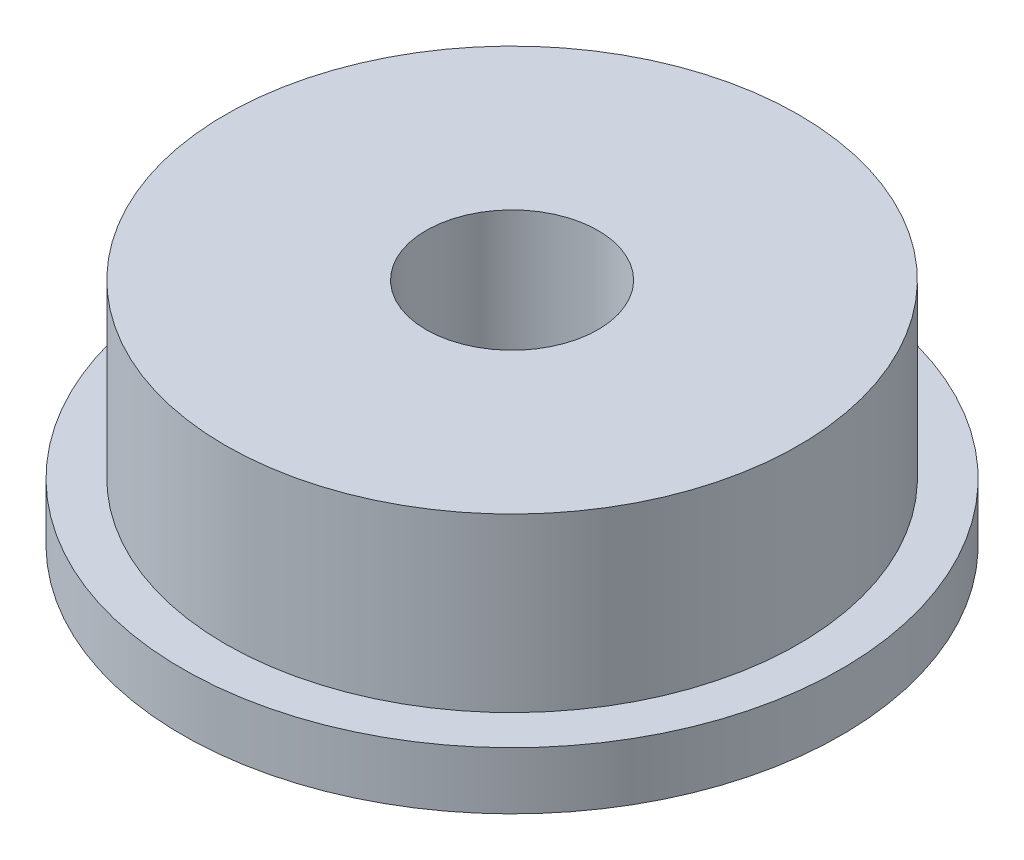
SolidWorks part; units mm, degrees
material "Liga de aço"
ref_plane "Plano frontal" through (0, 0, 0) normal (0, 0, 1) x (1, 0, 0)
ref_plane "Plano superior" through (0, 0, 0) normal (0, 1, 0) x (1, 0, 0)
ref_plane "Plano direito" through (0, 0, 0) normal (1, 0, 0) x (0, 0, -1)
sketch "Esboço1" plane through (0, 0, 0) normal (0, 1, 0) x (1, 0, 0)
  circle A0 centre (0, 0) radius 5
  dimension "D1" = 10
extrude "Ressalto-extrusão1" add sketch "Esboço1" along normal blind 4
sketch "Esboço3" plane through (0, 0, 0) normal (0, -1, 0) x (1, 0, 0)
  circle A0 centre (0, 0) radius 5.75
  dimension "D1" = 11.5
extrude "Ressalto-extrusão2" add sketch "Esboço3" against normal blind 1
sketch "Esboço2" plane through (0, 4, 0) normal (0, 1, 0) x (1, 0, 0)
  circle A0 centre (0, 0) radius 1.5
  dimension "D1" = 3
extrude "Corte-extrusão1" cut sketch "Esboço2" against normal blind 4
